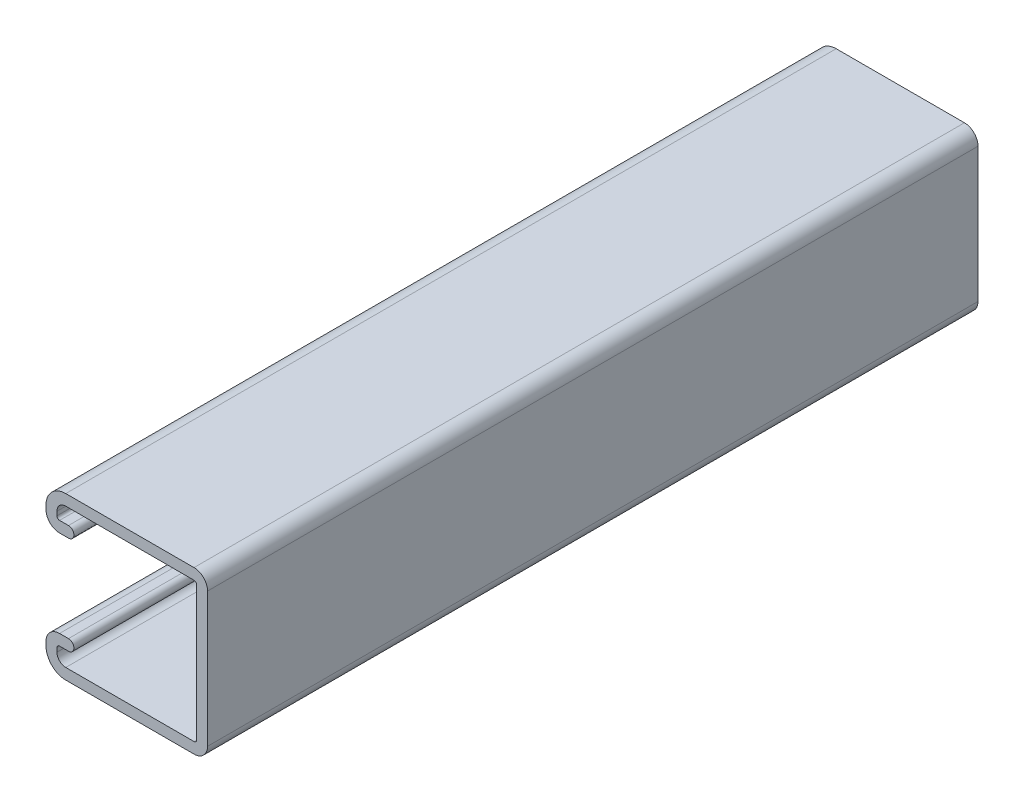
SolidWorks part; units mm, degrees
ref_plane "Front Plane" through (0, 0, 0) normal (0, 0, 1) x (1, 0, 0)
ref_plane "Top Plane" through (0, 0, 0) normal (0, 1, 0) x (1, 0, 0)
ref_plane "Right Plane" through (0, 0, 0) normal (1, 0, 0) x (0, 0, -1)
sketch "Sketch1" plane through (0, 0, 0) normal (0, 0, 1) x (1, 0, 0)
  line L0 (0, 0) -> (-41.275, 0) construction
  line L3 (-41.275, 20.6375) -> (0, 20.6375) construction
  line L4 (-41.275, 20.6375) -> (-41.275, -20.6375) construction
  line L5 (-41.275, -20.6375) -> (0, -20.6375) construction
  line L6 (0, 20.6375) -> (0, -20.6375) construction
  line L7 (-36.2267, 20.6375) -> (-3.4607, 20.6375)
  line L8 (0, 17.1767) -> (0, -17.1767)
  line L9 (-2.794, -17.1767) -> (-2.794, 17.1767)
  line L10 (-3.4608, 17.8435) -> (-36.2267, 17.8435)
  line L11 (-41.275, 15.5892) -> (-41.275, 14.5732)
  line L12 (-37.8142, 11.1125) -> (-35.5346, 11.1125)
  line L14 (-35.5346, 13.9065) -> (-37.8142, 13.9065)
  line L15 (-38.481, 14.5732) -> (-38.481, 15.5892)
  line L16 (-38.481, -14.5733) -> (-38.481, -15.5893)
  line L17 (-35.5346, -13.9065) -> (-37.8142, -13.9065)
  line L18 (-37.8142, -11.1125) -> (-35.5346, -11.1125)
  line L19 (-41.275, -15.5893) -> (-41.275, -14.5733)
  line L20 (-3.4607, -17.8435) -> (-36.2267, -17.8435)
  line L21 (-36.2267, -20.6375) -> (-3.4607, -20.6375)
  line L22 (-2.794, -20.6375) -> (-2.794, 20.6375) construction
  arc A1 (0, 17.1767) -> (-3.4607, 20.6375) centre (-3.4607, 17.1767) ccw
  arc A2 (-2.794, 17.1767) -> (-3.4608, 17.8435) centre (-3.4607, 17.1767) ccw
  arc A4 (-36.2267, 20.6375) -> (-41.275, 15.5892) centre (-36.2267, 15.5892) ccw
  arc A5 (-41.275, 14.5732) -> (-37.8142, 11.1125) centre (-37.8142, 14.5732) ccw
  arc A6 (-35.5346, 11.1125) -> (-35.5346, 13.9065) centre (-35.5346, 12.5095) ccw
  arc A7 (-37.8142, 13.9065) -> (-38.481, 14.5732) centre (-37.8142, 14.5732) cw
  arc A8 (-38.481, 15.5892) -> (-36.2267, 17.8435) centre (-36.2267, 15.5892) cw
  arc A9 (-38.481, -15.5893) -> (-36.2267, -17.8435) centre (-36.2267, -15.5893) ccw
  arc A10 (-37.8142, -13.9065) -> (-38.481, -14.5733) centre (-37.8142, -14.5733) ccw
  arc A11 (-35.5346, -11.1125) -> (-35.5346, -13.9065) centre (-35.5346, -12.5095) cw
  arc A12 (-41.275, -14.5733) -> (-37.8142, -11.1125) centre (-37.8142, -14.5733) cw
  arc A13 (-36.2267, -20.6375) -> (-41.275, -15.5893) centre (-36.2267, -15.5893) cw
  arc A14 (-2.794, -17.1767) -> (-3.4607, -17.8435) centre (-3.4607, -17.1767) cw
  arc A15 (0, -17.1767) -> (-3.4607, -20.6375) centre (-3.4607, -17.1767) cw
  point P24 (0, 20.6375)
  point P65 (-2.794, 0)
  dimension "D1" = 3.4608
  dimension "D2" = 5.0482
  dimension "D3" = 3.4608
  dimension "Ht." = 41.275
  dimension "Wd." = 41.275
  dimension "Thk." = 2.794
  dimension "D4" = 9.525
  dimension "D5" = 7.1374
extrude "Boss-Extrude1" add sketch "Sketch1" against normal mid plane 196.85
equation "\"7.875.0000in\"=24"
